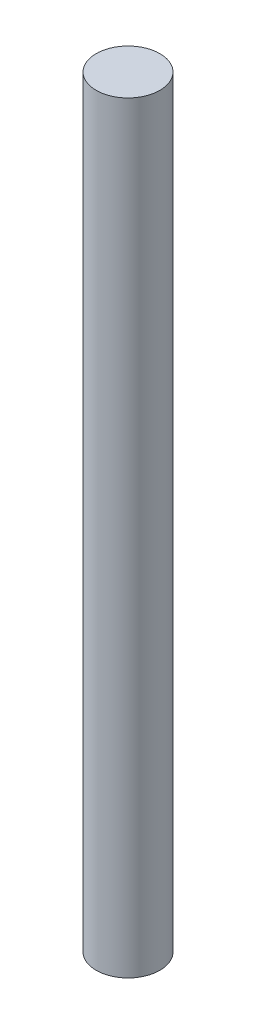
SolidWorks part; units mm, degrees
ref_plane "Alzado" through (0, 0, 0) normal (0, 0, 1) x (1, 0, 0)
ref_plane "Planta" through (0, 0, 0) normal (0, 1, 0) x (1, 0, 0)
ref_plane "Vista lateral" through (0, 0, 0) normal (1, 0, 0) x (0, 0, -1)
sketch "Croquis1" plane through (0, 0, 0) normal (0, 1, 0) x (1, 0, 0)
  circle A0 centre (0, 0) radius 4.7625
  dimension "D1" = 9.525
extrude "Saliente-Extruir1" add sketch "Croquis1" along normal blind 114
